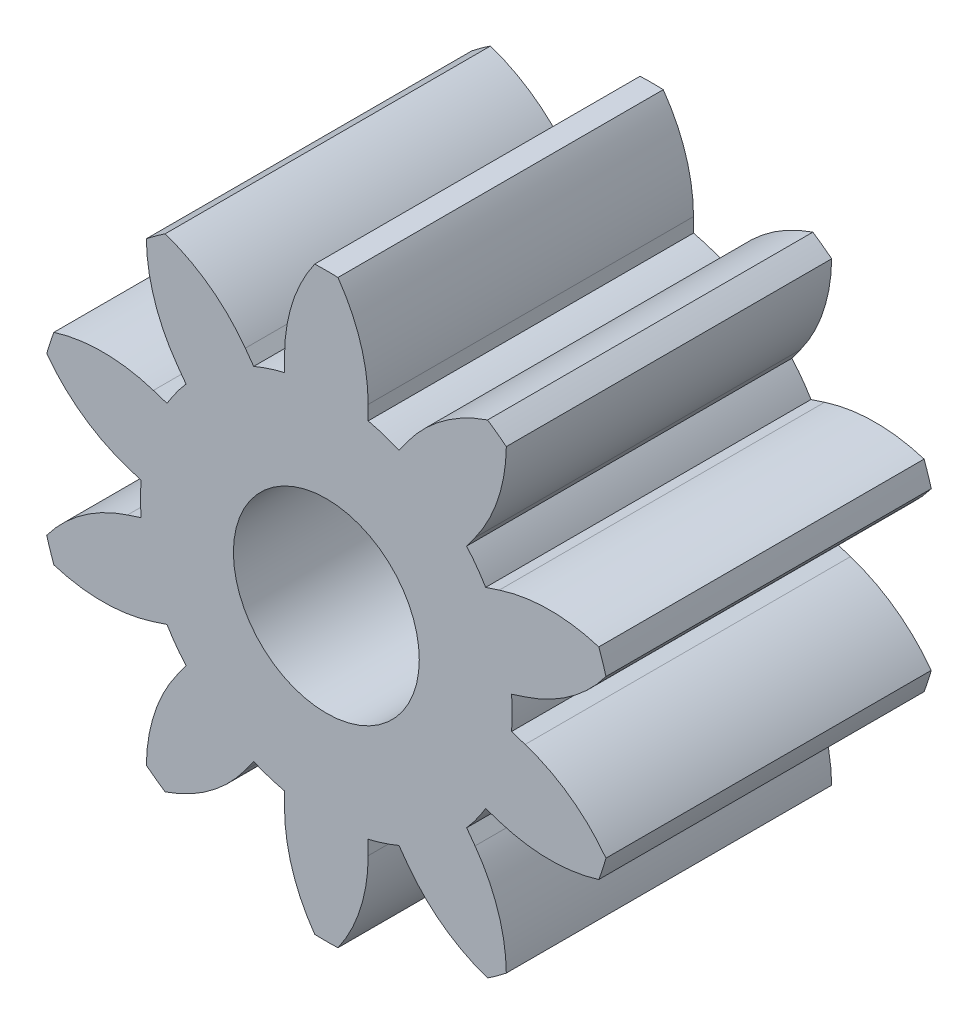
SolidWorks part; units mm, degrees
material "AISI 304"
ref_plane "Plano frontal" through (0, 0, 0) normal (0, 0, 1) x (1, 0, 0)
ref_plane "Plano superior" through (0, 0, 0) normal (0, 1, 0) x (1, 0, 0)
ref_plane "Plano direito" through (0, 0, 0) normal (1, 0, 0) x (0, 0, -1)
sketch "Esboço1" plane through (0, 0, 0) normal (0, 0, 1) x (1, 0, 0)
  line L0 (0, 0) -> (0, 3.125) construction
  line L1 (-0.45, 1.9487) -> (0.45, 1.9487) construction
  line L2 (0.45, 1.9487) -> (0.45, 2.1024)
  line L3 (-0.45, 1.9487) -> (-0.45, 2.1024)
  line L4 (-0.125, 3.1225) -> (0.125, 3.1225) construction
  line L5 (1.5095, 1.312) -> (1.5998, 1.4364)
  line L6 (0.7814, 1.841) -> (0.8717, 1.9654)
  line L7 (1.9924, 0.1742) -> (2.1385, 0.2217)
  line L8 (1.7143, 1.0302) -> (1.8604, 1.0776)
  line L9 (1.7143, -1.0302) -> (1.8604, -1.0776)
  line L10 (1.9924, -0.1742) -> (2.1385, -0.2217)
  line L11 (0.7814, -1.841) -> (0.8717, -1.9654)
  line L12 (1.5095, -1.312) -> (1.5998, -1.4364)
  line L13 (-0.45, -1.9487) -> (-0.45, -2.1024)
  line L14 (0.45, -1.9487) -> (0.45, -2.1024)
  line L15 (-1.5095, -1.312) -> (-1.5998, -1.4364)
  line L16 (-0.7814, -1.841) -> (-0.8717, -1.9654)
  line L17 (-1.9924, -0.1742) -> (-2.1385, -0.2217)
  line L18 (-1.7143, -1.0302) -> (-1.8604, -1.0776)
  line L19 (-1.7143, 1.0302) -> (-1.8604, 1.0776)
  line L20 (-1.9924, 0.1742) -> (-2.1385, 0.2217)
  line L21 (-0.7814, 1.841) -> (-0.8717, 1.9654)
  line L22 (-1.5095, 1.312) -> (-1.5998, 1.4364)
  circle A0 centre (0, 0) radius 2
  circle A1 centre (0, 0) radius 2.15 construction
  arc A2 (0.125, 3.1225) -> (-0.125, 3.1225) centre (0, 0) ccw
  arc A3 (0.125, 3.1225) -> (-0.125, 3.1225) centre (0, 0) ccw
  arc A4 (0.45, 2.1024) -> (0.125, 3.1225) centre (-1.3135, 2.1024) ccw
  arc A5 (-0.45, 2.1024) -> (-0.125, 3.1225) centre (1.3135, 2.1024) cw
  arc A6 (1.5998, 1.4364) -> (1.9365, 2.4527) centre (0.1731, 2.4729) ccw
  arc A7 (1.9365, 2.4527) -> (1.7342, 2.5996) centre (0, 0) ccw
  arc A8 (0.8717, 1.9654) -> (1.7342, 2.5996) centre (2.2984, 0.9288) cw
  arc A9 (2.1385, 0.2217) -> (3.0083, 0.846) centre (1.5936, 1.8989) ccw
  arc A10 (3.0083, 0.846) -> (2.931, 1.0838) centre (0, 0) ccw
  arc A11 (1.8604, 1.0776) -> (2.931, 1.0838) centre (2.4054, -0.5995) cw
  arc A12 (1.8604, -1.0776) -> (2.931, -1.0838) centre (2.4054, 0.5995) ccw
  arc A13 (2.931, -1.0838) -> (3.0083, -0.846) centre (0, 0) ccw
  arc A14 (2.1385, -0.2217) -> (3.0083, -0.846) centre (1.5936, -1.8989) cw
  arc A15 (0.8717, -1.9654) -> (1.7342, -2.5996) centre (2.2984, -0.9288) ccw
  arc A16 (1.7342, -2.5996) -> (1.9365, -2.4527) centre (0, 0) ccw
  arc A17 (1.5998, -1.4364) -> (1.9365, -2.4527) centre (0.1731, -2.4729) cw
  arc A18 (-0.45, -2.1024) -> (-0.125, -3.1225) centre (1.3135, -2.1024) ccw
  arc A19 (-0.125, -3.1225) -> (0.125, -3.1225) centre (0, 0) ccw
  arc A20 (0.45, -2.1024) -> (0.125, -3.1225) centre (-1.3135, -2.1024) cw
  arc A21 (-1.5998, -1.4364) -> (-1.9365, -2.4527) centre (-0.1731, -2.4729) ccw
  arc A22 (-1.9365, -2.4527) -> (-1.7342, -2.5996) centre (0, 0) ccw
  arc A23 (-0.8717, -1.9654) -> (-1.7342, -2.5996) centre (-2.2984, -0.9288) cw
  arc A24 (-2.1385, -0.2217) -> (-3.0083, -0.846) centre (-1.5936, -1.8989) ccw
  arc A25 (-3.0083, -0.846) -> (-2.931, -1.0838) centre (0, 0) ccw
  arc A26 (-1.8604, -1.0776) -> (-2.931, -1.0838) centre (-2.4054, 0.5995) cw
  arc A27 (-1.8604, 1.0776) -> (-2.931, 1.0838) centre (-2.4054, -0.5995) ccw
  arc A28 (-2.931, 1.0838) -> (-3.0083, 0.846) centre (0, 0) ccw
  arc A29 (-2.1385, 0.2217) -> (-3.0083, 0.846) centre (-1.5936, 1.8989) cw
  arc A30 (-0.8717, 1.9654) -> (-1.7342, 2.5996) centre (-2.2984, 0.9288) ccw
  arc A31 (-1.7342, 2.5996) -> (-1.9365, 2.4527) centre (0, 0) ccw
  arc A32 (-1.5998, 1.4364) -> (-1.9365, 2.4527) centre (-0.1731, 2.4729) cw
  point P9 (0, 1.9487)
  point P14 (0, 3.1225)
  dimension "D1" = 4
  dimension "D2" = 6.25
  dimension "D3" = 4.3
  dimension "D4" = 0.9
  dimension "D5" = 0.25
  dimension "D6" = 10
extrude "Ressalto-extrusão1" add sketch "Esboço1" along normal blind 3.5 contours A0 | A32 L22 A0 L21 A30 A31 | A5 L3 A0 L2 A4 A2 | A8 L6 A0 L5 A6 A7 | A11 L8 A0 L7 A9 A10 | A14 L10 A0 L9 A12 A13 | A17 L12 A0 L11 A15 A16 | A20 L14 A0 L13 A18 A19 | A23 L16 A0 L15 A21 A22 | A26 L18 A0 L17 A24 A25 | A29 L20 A0 L19 A27 A28
sketch "Esboço2" plane through (0, 0, 3.5) normal (0, 0, 1) x (1, 0, 0)
  circle A0 centre (0, 0) radius 1
  dimension "D1" = 2
extrude "Corte-extrusão1" cut sketch "Esboço2" against normal through all
